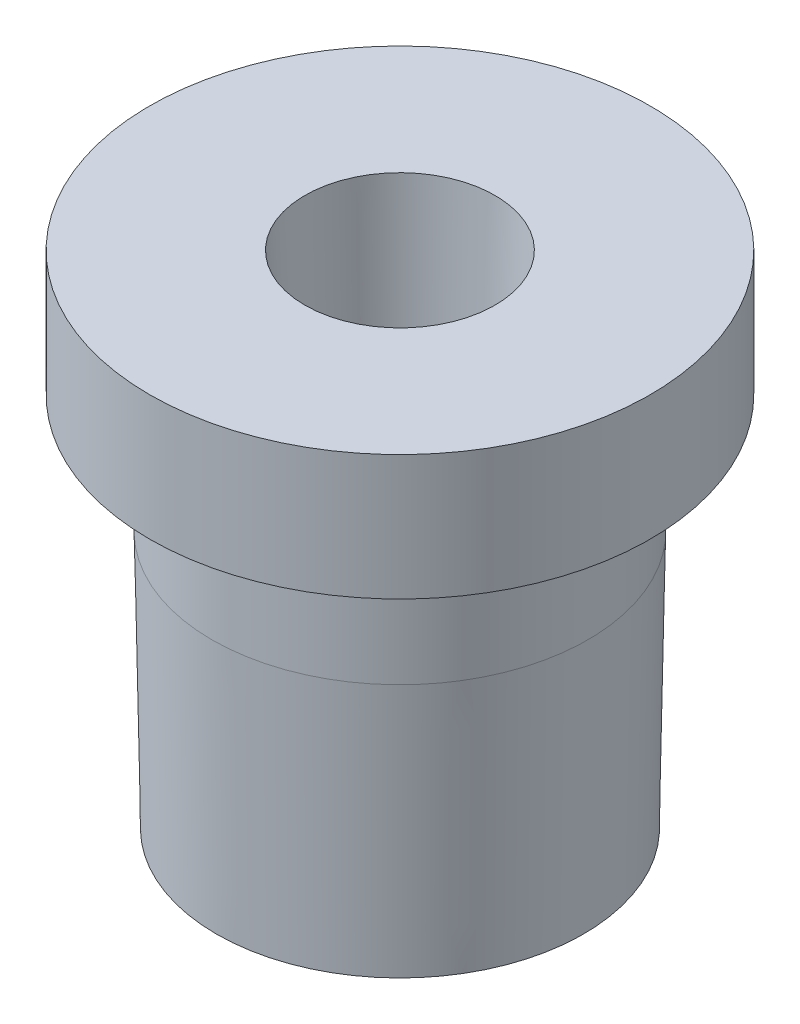
SolidWorks part; units mm, degrees
material "AISI 304"
ref_plane "Front" through (0, 0, 0) normal (0, 0, 1) x (1, 0, 0)
ref_plane "Top" through (0, 0, 0) normal (0, 1, 0) x (1, 0, 0)
ref_plane "Right" through (0, 0, 0) normal (1, 0, 0) x (0, 0, -1)
sketch "Sketch1" plane through (0, 0, 0) normal (0, 1, 0) x (1, 0, 0)
  circle A0 centre (0, 0) radius 9.5428
  dimension "D1" = 19.0856
extrude "Boss-Extrude1" add sketch "Sketch1" along normal blind 25.4
sketch "Sketch2" plane through (0, 25.4, 0) normal (0, 1, 0) x (1, 0, 0)
  circle A0 centre (0, 0) radius 12.7
  dimension "D1" = 25.4
extrude "Boss-Extrude2" add sketch "Sketch2" against normal blind 6.35
hole_wizard "R (0.339) Diameter Hole1" positions "Sketch7" profile "Sketch8" hole size "R" standard "ANSI Inch" end condition through all
sketch "Sketch7" plane through (0, 25.4, 0) normal (0, 1, 0) x (1, 0, 0)
  point P0 (0, 0)
sketch "Sketch8" plane through (0, 25.4, 0) normal (1, 0, 0) x (0, 0, 1)
  line L0 (0, 0) -> (0, 25.4)
  line L1 (0, 25.4) -> (4.3053, 25.4)
  line L2 (4.3053, 25.4) -> (4.3053, 0)
  line L5 (4.3053, 0) -> (0, 0)
  line L11 (0, -6.35) -> (0, 107.95) construction
  dimension "Thru Hole Dia." = 8.6106
  dimension "Thru Hole Depth" = 25.4
hole_wizard "1/8 NPT Tapped Hole1" positions "Sketch3" profile "Sketch4" size "1/8" standard "ANSI Inch"
sketch "Sketch3" plane through (0, 25.4, 0) normal (0, 1, 0) x (1, 0, 0)
  point P0 (0, 0)
sketch "Sketch4" plane through (0, 25.4, 0) normal (1, 0, 0) x (0, 0, 1)
  line L0 (0, 0) -> (0, 14.478)
  line L1 (4.2164, 11.9445) -> (0, 14.478)
  line L2 (-4.2164, 11.9445) -> (0, 14.478) construction
  line L3 (4.2164, 11.9445) -> (4.2164, 9.652)
  line L4 (4.2164, 9.652) -> (4.5374, 9.652)
  line L5 (4.5374, 9.652) -> (4.8264, 0)
  line L6 (-4.5374, 9.652) -> (-4.8264, 0) construction
  line L7 (4.8264, 0) -> (0, 0)
  line L8 (0, -6.35) -> (0, 107.95) construction
  line L11 (-4.2164, 9.652) -> (-4.5374, 9.652) construction
  dimension "Tap Drill Dia." = 8.4328
  dimension "Tap Drill Depth" = 14.478
  dimension "Thread Dia." = 9.6528
  dimension "Thread Angle" = 3.43
  dimension "Thread Depth" = 9.652
  dimension "Drill Angle" = 118
cosmetic thread "Hole Thread1" parameters "D1"=9.652, "D2"=10.45
hole_wizard "1/8 NPT Tapped Hole2" positions "Sketch5" profile "Sketch6" size "1/8" standard "ANSI Inch"
sketch "Sketch5" plane through (0, 0, 0) normal (0, -1, 0) x (-1, 0, 0)
  point P0 (0, 0)
sketch "Sketch6" plane through (0, 0, 0) normal (1, 0, 0) x (0, 0, -1)
  line L0 (0, 0) -> (0, 14.478)
  line L1 (4.2164, 11.9445) -> (0, 14.478)
  line L2 (-4.2164, 11.9445) -> (0, 14.478) construction
  line L3 (4.2164, 11.9445) -> (4.2164, 9.652)
  line L4 (4.2164, 9.652) -> (4.5374, 9.652)
  line L5 (4.5374, 9.652) -> (4.8264, 0)
  line L6 (-4.5374, 9.652) -> (-4.8264, 0) construction
  line L7 (4.8264, 0) -> (0, 0)
  line L8 (0, -6.35) -> (0, 107.95) construction
  line L11 (-4.2164, 9.652) -> (-4.5374, 9.652) construction
  dimension "Tap Drill Dia." = 8.4328
  dimension "Tap Drill Depth" = 14.478
  dimension "Thread Dia." = 9.6528
  dimension "Thread Angle" = 3.43
  dimension "Thread Depth" = 9.652
  dimension "Drill Angle" = 118
cosmetic thread "Hole Thread2" parameters "D1"=9.652, "D2"=10.45
ref_axis "Axis1" through (0, 19.05, 0) along (0, -1, 0)
sketch "Sketch9" plane through (0, 0, 0) normal (1, 0, 0) x (0, 0, -1)
  line L0 (-9.315, 0) -> (-9.5428, 13.05)
  line L1 (-9.5428, 0) -> (9.5428, 0) construction
  line L2 (-9.5428, 19.05) -> (-9.5428, 0) construction
  line L3 (-9.5428, 13.05) -> (-9.5428, 0)
  line L4 (-9.5428, 0) -> (-9.315, 0)
  dimension "D1" = 6
  dimension "D2" = 1
revolve "Cut-Revolve1" cut sketch "Sketch9" angle 360 about axis through (0, 19.05, 0) along (0, -1, 0)
